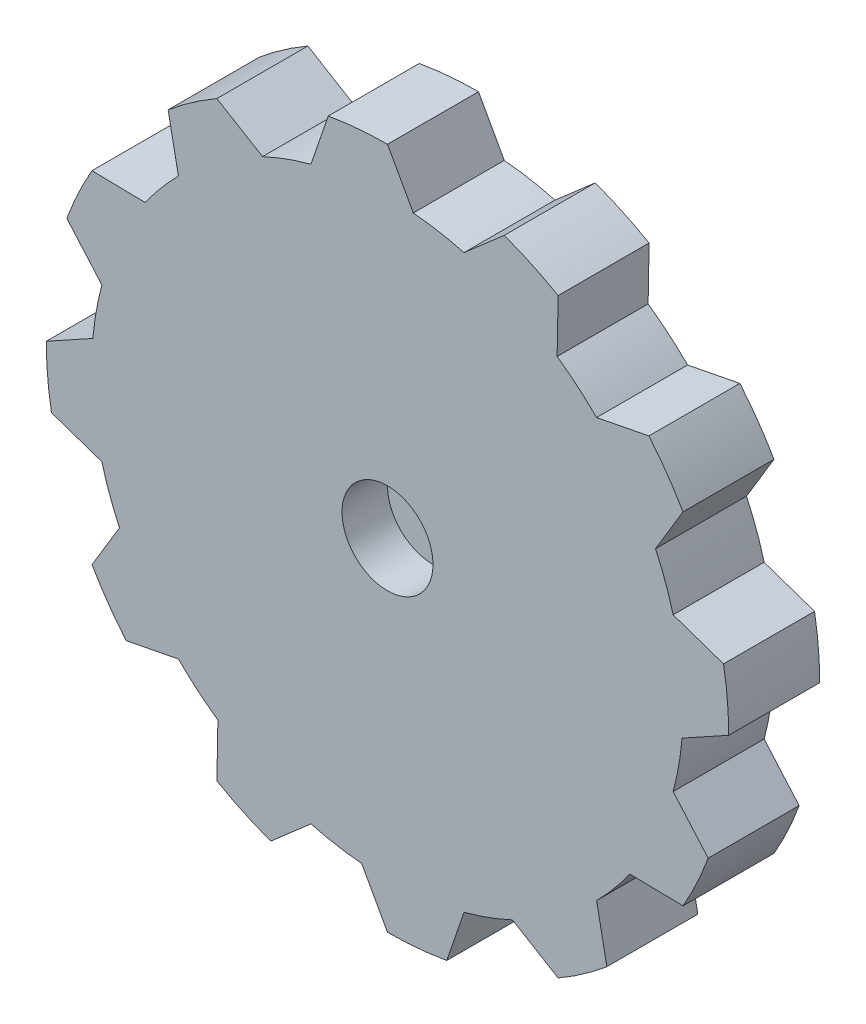
SolidWorks part; units mm, degrees
ref_plane "Alzado" through (0, 0, 0) normal (0, 0, 1) x (1, 0, 0)
ref_plane "Planta" through (0, 0, 0) normal (0, 1, 0) x (1, 0, 0)
ref_plane "Vista lateral" through (0, 0, 0) normal (1, 0, 0) x (0, 0, -1)
sketch "Croquis1" plane through (0, 0, 0) normal (0, 0, 1) x (1, 0, 0)
  circle A0 centre (0, 0) radius 75
  dimension "D1" = 150
extrude "Saliente-Extruir1" add sketch "Croquis1" along normal blind 20
sketch "Croquis3" plane through (0, 0, 20) normal (0, 0, 1) x (1, 0, 0)
  circle A0 centre (0, 0) radius 10
  dimension "D1" = 20
extrude "Cortar-Extruir2" cut sketch "Croquis3" against normal blind 10
sketch "Croquis2" plane through (0, 0, 20) normal (0, 0, 1) x (1, 0, 0)
  line L0 (0, 0) -> (75, 0) construction
  line L1 (0, 0) -> (70.4769, -25.6515) construction
  line L2 (0, 0) -> (64.7527, -5.6651) construction
  line L3 (0, 0) -> (62.7852, -16.8232) construction
  line L4 (64.7527, -5.6651) -> (75, 0)
  line L6 (62.7852, -16.8232) -> (70.4769, -25.6515)
  arc A0 (62.7852, -16.8232) -> (64.7527, -5.6651) centre (0, 0) ccw
  arc A1 (70.4769, -25.6515) -> (75, 0) centre (0, 0) ccw
  point P10 (0, 0)
  dimension "D2" = 5
  dimension "D1" = 5
  dimension "D5" = 75
  dimension "D4" = 65
  dimension "D3" = 20
extrude "Cortar-Extruir3" cut sketch "Croquis2" against normal blind 20
pattern_circular "MatrizC3" count 12 every 30 about axis through (0, 0, 0) along (0, 0, 1) of "Cortar-Extruir3", "Cortar-Extruir2"
